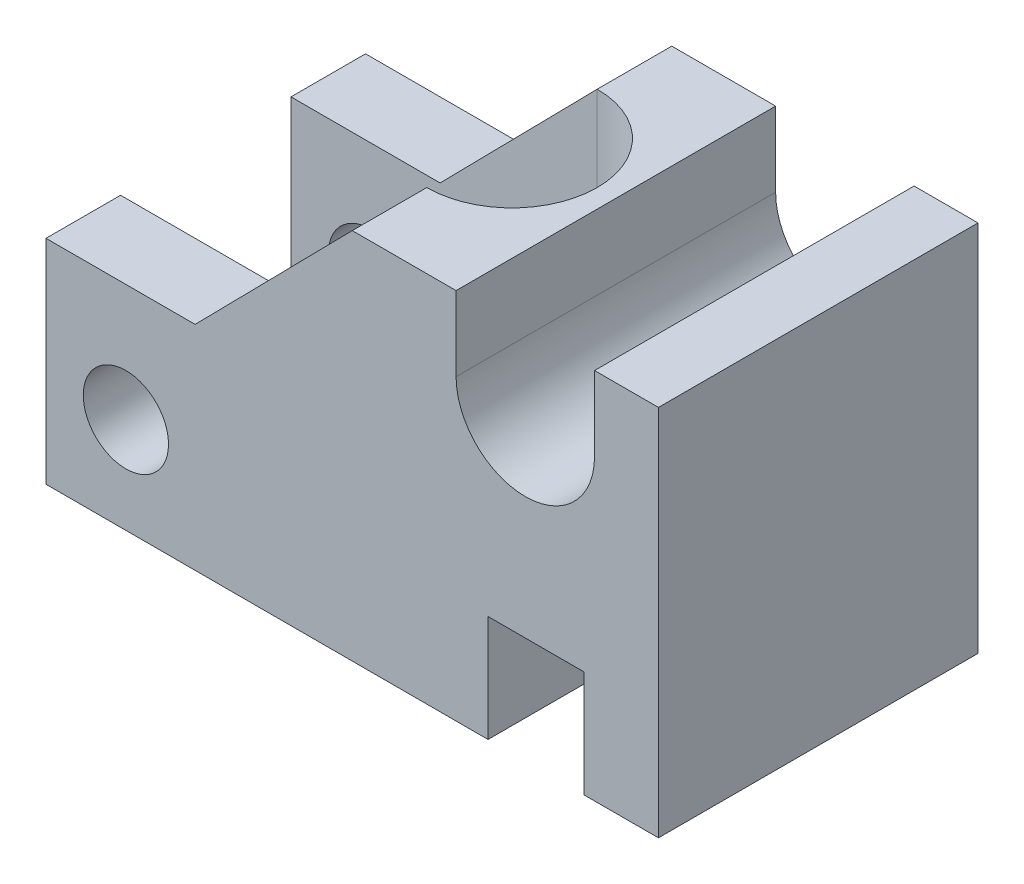
SolidWorks part; units mm, degrees
ref_plane "Front Plane" through (0, 0, 0) normal (0, 0, 1) x (1, 0, 0)
ref_plane "Top Plane" through (0, 0, 0) normal (0, 1, 0) x (1, 0, 0)
ref_plane "Right Plane" through (0, 0, 0) normal (1, 0, 0) x (0, 0, -1)
sketch "Sketch1" plane through (0, 0, 0) normal (0, 0, 1) x (1, 0, 0)
  line L0 (0, 0) -> (38.4663, 0)
  line L1 (38.4663, 0) -> (38.4663, 20)
  line L2 (38.4663, 20) -> (56.4663, 20)
  line L3 (56.4663, 20) -> (56.4663, 0)
  line L4 (56.4663, 0) -> (70.4663, 0)
  line L5 (70.4663, 0) -> (70.4663, 70)
  line L6 (70.4663, 70) -> (58.4663, 70)
  line L7 (12.9663, 70) -> (-16.5337, 40)
  line L8 (-16.5337, 40) -> (-44.5337, 40)
  line L9 (-44.5337, 40) -> (-44.5337, 0)
  line L10 (-44.5337, 0) -> (0, 0)
  line L11 (12.9663, 70) -> (12.9663, 0)
  line L16 (32.4663, 70) -> (12.9663, 70)
  line L17 (32.4663, 70) -> (32.4663, 56)
  line L18 (58.4663, 70) -> (58.4663, 56)
  arc A1 (32.4663, 56) -> (58.4663, 56) centre (45.4663, 56) ccw
  circle A2 centre (-29.5337, 18) radius 8
  point P16 (0, 0)
  dimension "D9" = 25
  dimension "D13" = 16
  dimension "D1" = 115
  dimension "D2" = 18
  dimension "D3" = 14
  dimension "D4" = 20
  dimension "D5" = 28
  dimension "D6" = 40
  dimension "D7" = 57.5
  dimension "D8" = 70
  dimension "D10" = 26
  dimension "D11" = 18
  dimension "D12" = 15
  dimension "D14" = 14
extrude "Boss-Extrude1" add sketch "Sketch1" along normal blind 60 contours A1 L17 L16 L11 L0 L1 L2 L3 L4 L5 L6 L18 | L11 L7 L8 L9 L10 L0 A2
sketch "Sketch2" plane through (0, 70, 0) normal (0, 1, 0) x (1, 0, 0)
  line L0 (12.9663, -60) -> (12.9663, 0) construction
  line L1 (12.9663, -14) -> (-56.3085, -14)
  line L2 (12.9663, -46) -> (-56.3085, -46)
  line L3 (-56.3085, -46) -> (-56.3085, -14)
  arc A0 (12.9663, -46) -> (12.9663, -14) centre (12.9663, -30) ccw
  dimension "D1" = 32
extrude "Cut-Extrude1" cut sketch "Sketch2" against normal through all
